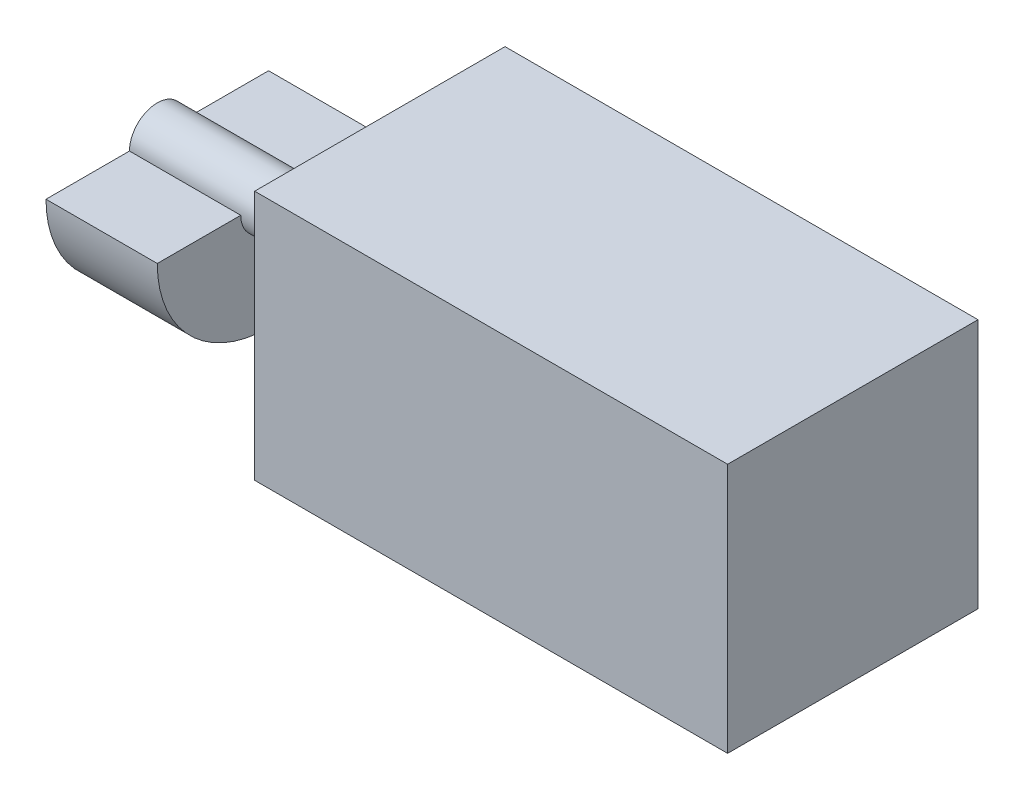
SolidWorks part; units mm, degrees
ref_plane "Front Plane" through (0, 0, 0) normal (0, 0, 1) x (1, 0, 0)
ref_plane "Top Plane" through (0, 0, 0) normal (0, 1, 0) x (1, 0, 0)
ref_plane "Right Plane" through (0, 0, 0) normal (1, 0, 0) x (0, 0, -1)
sketch "Sketch1" plane through (0, 0, 0) normal (0, 1, 0) x (1, 0, 0)
  line L1 (4.25, 2.25) -> (-4.25, 2.25)
  line L2 (4.25, 2.25) -> (4.25, -2.25)
  line L3 (4.25, -2.25) -> (-4.25, -2.25)
  line L4 (-4.25, 2.25) -> (-4.25, -2.25)
  line L5 (4.25, 2.25) -> (-4.25, -2.25) construction
  line L6 (4.25, -2.25) -> (-4.25, 2.25) construction
  point P0 (0, 0)
  dimension "D1" = 4.5
  dimension "D2" = 8.5
extrude "Boss-Extrude1" add sketch "Sketch1" along normal blind 4.5
sketch "Sketch2" plane through (-4.25, 0, 0) normal (-1, 0, 0) x (0, 0, 1)
  line L0 (-2.25, 0) -> (2.25, 4.5) construction
  circle A0 centre (0, 2.25) radius 1.25
  dimension "D1" = 2.5
extrude "Boss-Extrude2" add sketch "Sketch2" along normal blind 1
sketch "Sketch3" plane through (-5.25, 0, 0) normal (-1, 0, 0) x (0, 0, 1)
  circle A0 centre (0, 2.25) radius 0.5
  dimension "D1" = 1
extrude "Boss-Extrude3" add sketch "Sketch3" along normal blind 1
sketch "Sketch4" plane through (-6.25, 0, 0) normal (-1, 0, 0) x (0, 0, 1)
  circle A0 centre (0, 2.25) radius 2
  dimension "D1" = 4
extrude "Boss-Extrude4" add sketch "Sketch4" along normal blind 2
sketch "Sketch5" plane through (-8.25, 0, 0) normal (-1, 0, 0) x (0, 0, 1)
  line L0 (-2, 2.25) -> (-0.5, 2.25)
  line L1 (0.5, 2.25) -> (2, 2.25)
  circle A0 centre (0, 2.25) radius 0.5
  circle A1 centre (0, 2.25) radius 2 construction
  circle A2 centre (0, 2.25) radius 2
  circle M1 centre (0, 2.25) radius 2
  dimension "D1" = 1
extrude "Cut-Extrude1" cut sketch "Sketch5" against normal blind 2 contours A0 L1 L0 M1
